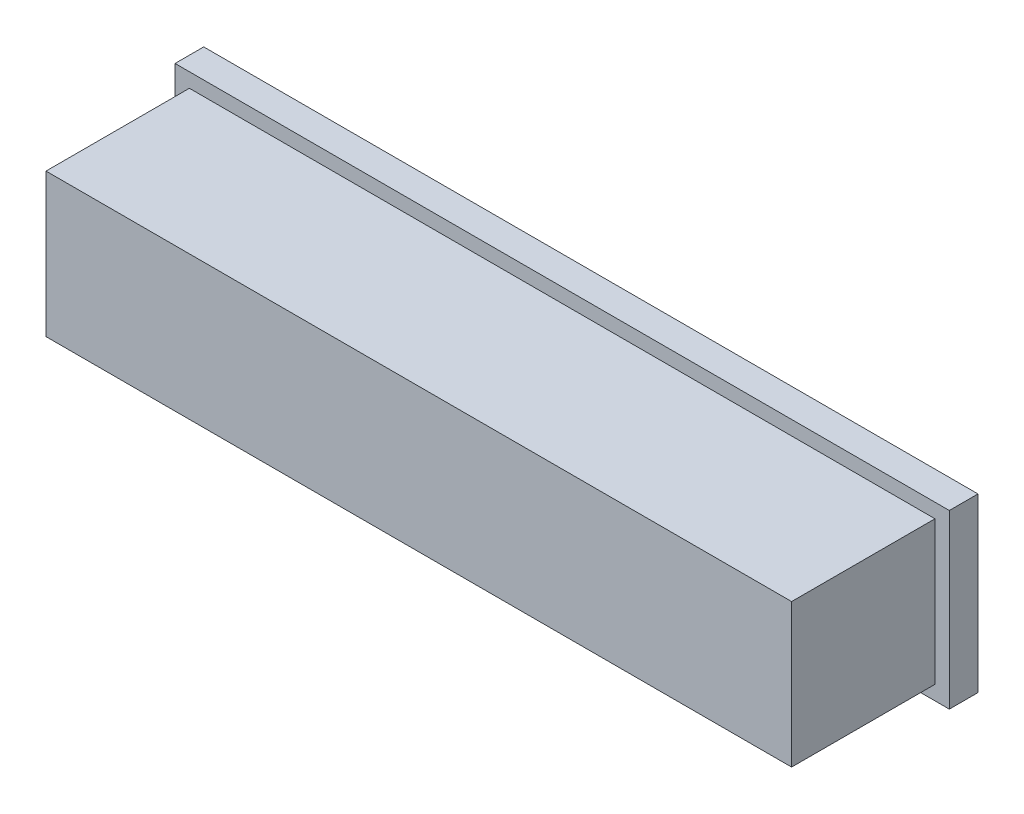
SolidWorks part; units mm, degrees
ref_plane "Ebene vorne" through (0, 0, 0) normal (0, 0, 1) x (1, 0, 0)
ref_plane "Ebene oben" through (0, 0, 0) normal (0, 1, 0) x (1, 0, 0)
ref_plane "Ebene rechts" through (0, 0, 0) normal (1, 0, 0) x (0, 0, -1)
sketch "Skizze1" plane through (0, 0, 0) normal (0, 0, 1) x (1, 0, 0)
  line L1 (-135, 30) -> (135, 30)
  line L2 (-135, 30) -> (-135, -30)
  line L3 (-135, -30) -> (135, -30)
  line L4 (135, 30) -> (135, -30)
  line L5 (-135, 30) -> (135, -30) construction
  line L6 (-135, -30) -> (135, 30) construction
  point P0 (0, 0)
  dimension "D1" = 60
  dimension "D2" = 270
extrude "Aufsatz-Linear austragen1" add sketch "Skizze1" along normal blind 10
sketch "Skizze2" plane through (0, 0, 10) normal (0, 0, 1) x (1, 0, 0)
  line L1 (-130, 25) -> (130, 25)
  line L2 (-130, 25) -> (-130, -25)
  line L3 (-130, -25) -> (130, -25)
  line L4 (130, 25) -> (130, -25)
  line L5 (-130, 25) -> (130, -25) construction
  line L6 (-130, -25) -> (130, 25) construction
  point P0 (0, 0)
  dimension "D1" = 260
  dimension "D2" = 50
extrude "Aufsatz-Linear austragen2" add sketch "Skizze2" along normal blind 50
